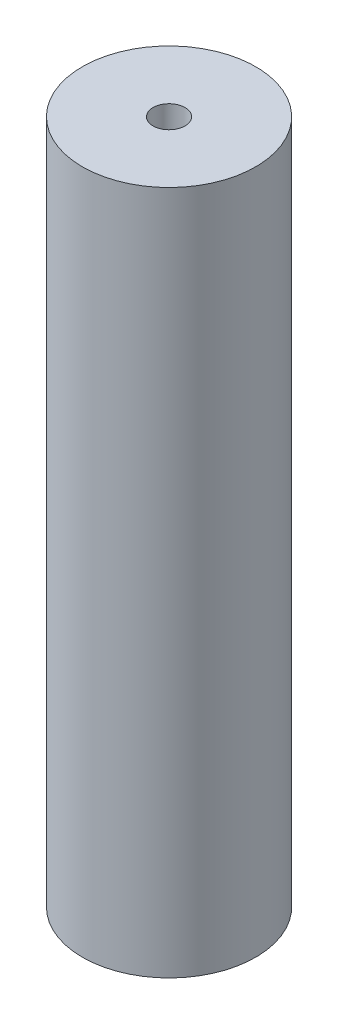
SolidWorks part; units mm, degrees
material "Epoxy, Unfilled"
ref_plane "Front Plane" through (0, 0, 0) normal (0, 0, 1) x (1, 0, 0)
ref_plane "Top Plane" through (0, 0, 0) normal (0, 1, 0) x (1, 0, 0)
ref_plane "Right Plane" through (0, 0, 0) normal (1, 0, 0) x (0, 0, -1)
sketch "Sketch1" plane through (0, 0, 0) normal (0, 1, 0) x (1, 0, 0)
  circle A0 centre (0, 0) radius 19
  circle A1 centre (0, 0) radius 3.5
extrude "Boss-Extrude1" add sketch "Sketch1" along normal blind 150
